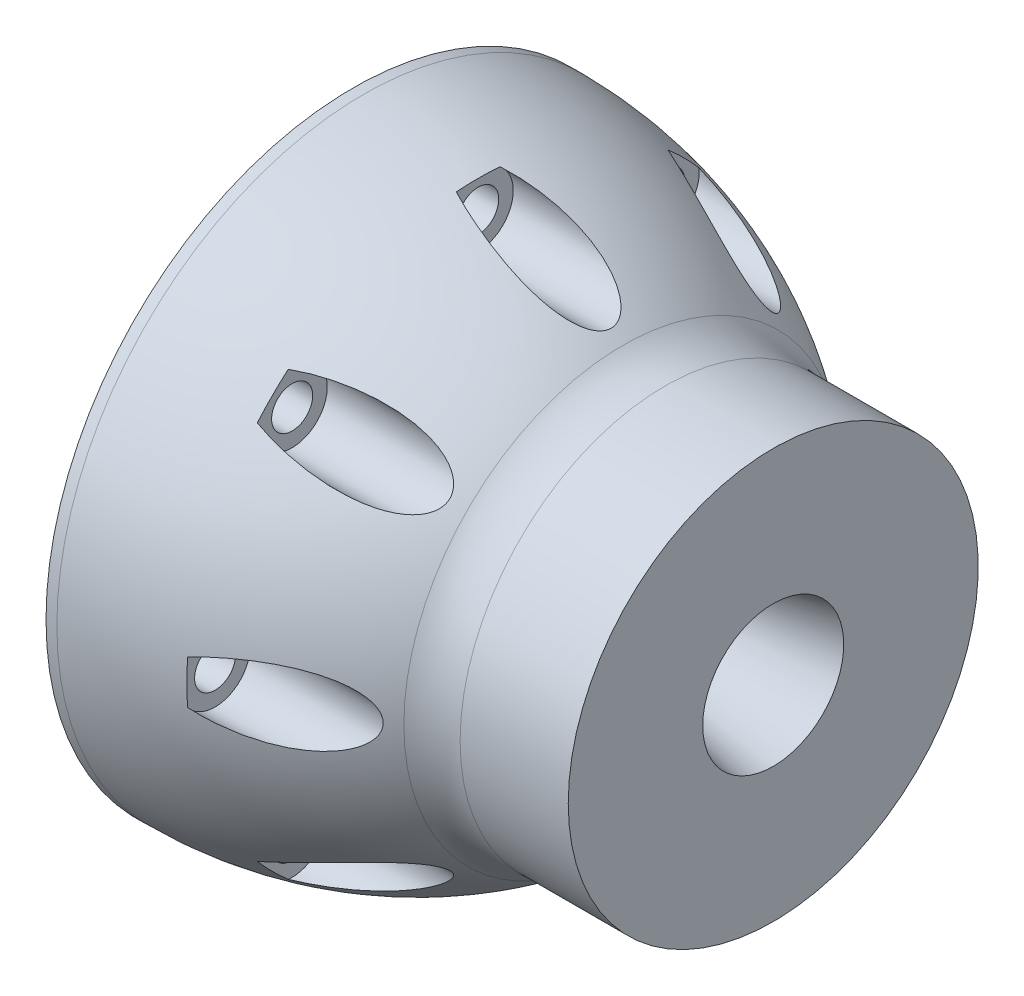
SolidWorks part; units mm, degrees
ref_plane "Front Plane" through (0, 0, 0) normal (0, 0, 1) x (1, 0, 0)
ref_plane "Top Plane" through (0, 0, 0) normal (0, 1, 0) x (1, 0, 0)
ref_plane "Right Plane" through (0, 0, 0) normal (1, 0, 0) x (0, 0, -1)
sketch "Model" plane through (0, 0, 0) normal (0, 0, 1) x (1, 0, 0)
  line L0 (0, 19.051) -> (31.9536, 19.051)
  line L1 (38.3809, 16.3887) -> (49.0299, 5.7397)
  line L2 (0, 0) -> (61.8717, 0) construction
  arc A0 (38.3809, 16.3887) -> (31.9536, 19.051) centre (31.9536, 9.9615) ccw
  arc A1 (49.0299, 5.7397) -> (50.8, 5.0065) centre (50.8, 7.5097) ccw
  arc A2 (50.8, 5.0065) -> (51.2904, 5.055) centre (50.8, 7.5097) ccw
  spline S0 degree 2 poles (51.2904, 5.055) (61.5184, 7.0984) (61.8717, 7.148) knots 0 0 0 1 1 1
  text T0 "Vortex_Chamber_Cold_Wall" font "SWTXT" height 5
sketch "Sketch2" plane through (0, 0, 0) normal (0, 0, 1) x (1, 0, 0)
  line L0 (61.8717, 7.148) -> (51.2904, 5.055)
  line L1 (49.0299, 5.7397) -> (38.3809, 16.3887)
  line L2 (31.9536, 19.051) -> (25.6036, 19.051)
  line L3 (0, 19.051) -> (31.9536, 19.051) construction
  line L4 (25.6036, 19.051) -> (25.6036, 22.225)
  line L5 (0, 0) -> (61.8717, 0) construction
  line L6 (25.6036, 22.225) -> (19.2536, 22.225)
  line L7 (19.2536, 22.225) -> (19.2536, 31.115)
  line L8 (19.2536, 31.115) -> (20.3519, 31.115)
  line L9 (50.9079, 20.7844) -> (61.8717, 20.7844)
  line L10 (61.8717, 20.7844) -> (61.8717, 7.148)
  arc A0 (51.2904, 5.055) -> (50.8, 5.0065) centre (50.7951, 7.5588) cw
  arc A1 (50.8, 5.0065) -> (49.0299, 5.7397) centre (50.7953, 7.4983) cw
  arc A2 (38.3809, 16.3887) -> (31.9536, 19.051) centre (31.9536, 9.9614) ccw
  arc A3 (20.3519, 31.115) -> (46.6468, 22.225) centre (20.3519, -12.2178) cw
  arc A4 (46.6468, 22.225) -> (50.9079, 20.7844) centre (50.9079, 27.8064) ccw
  point P21 (19.2536, 26.67)
  point P29 (41.1566, 25.4031)
  point P31 (50.307, 23.0502)
  point P32 (41.2438, 25.4903)
  point P33 (52.0499, 20.7844)
  point P34 (43.5096, 24.2702)
  point P35 (46.6468, 22.225)
  dimension "D1" = 6.35
  dimension "D2" = 22.225
  dimension "D3" = 26.67
  dimension "D4" = 6.35
revolve "Revolve1" add sketch "Sketch2" angle 360 about L2
sketch "Sketch3" plane through (19.2536, 0, 0) normal (-1, 0, 0) x (0, 0, 1)
  line L0 (0, 22.225) -> (0, 31.115) construction
  circle A0 centre (0, 26.67) radius 3.556
  circle A1 centre (0, 0) radius 22.225 construction
  circle A2 centre (0, 0) radius 22.225 construction
  circle A3 centre (0, 0) radius 31.115 construction
  point P11 (0, 26.67)
  dimension "D1" = 7.112
extrude "Cut-Extrude1" cut sketch "Sketch3" against normal up to surface (29.9182 mm away) from offset 12.7 up to face at (61.8717, 0, 20.7844) offset against normal yes
sketch "Sketch4" plane through (31.9536, 0, 0) normal (1, 0, 0) x (0, 0, -1)
  circle A0 centre (0, 26.67) radius 2.0828
  dimension "D1" = 4.1656
extrude "Cut-Extrude2" cut sketch "Sketch4" against normal up to surface (12.7 mm away) up to face at (19.2536, 0, 22.225)
pattern_circular "CirPattern1" count 8 over 360 about axis through (0, 0, 0) along (1, 0, 0) of "Cut-Extrude2", "Cut-Extrude1"
sketch "Sketch5" plane through (0, 0, 0) normal (0, 0, 1) x (1, 0, 0)
  line L0 (25.6036, 19.051) -> (-53.7714, 19.051)
  dimension "D1" = 85.725
